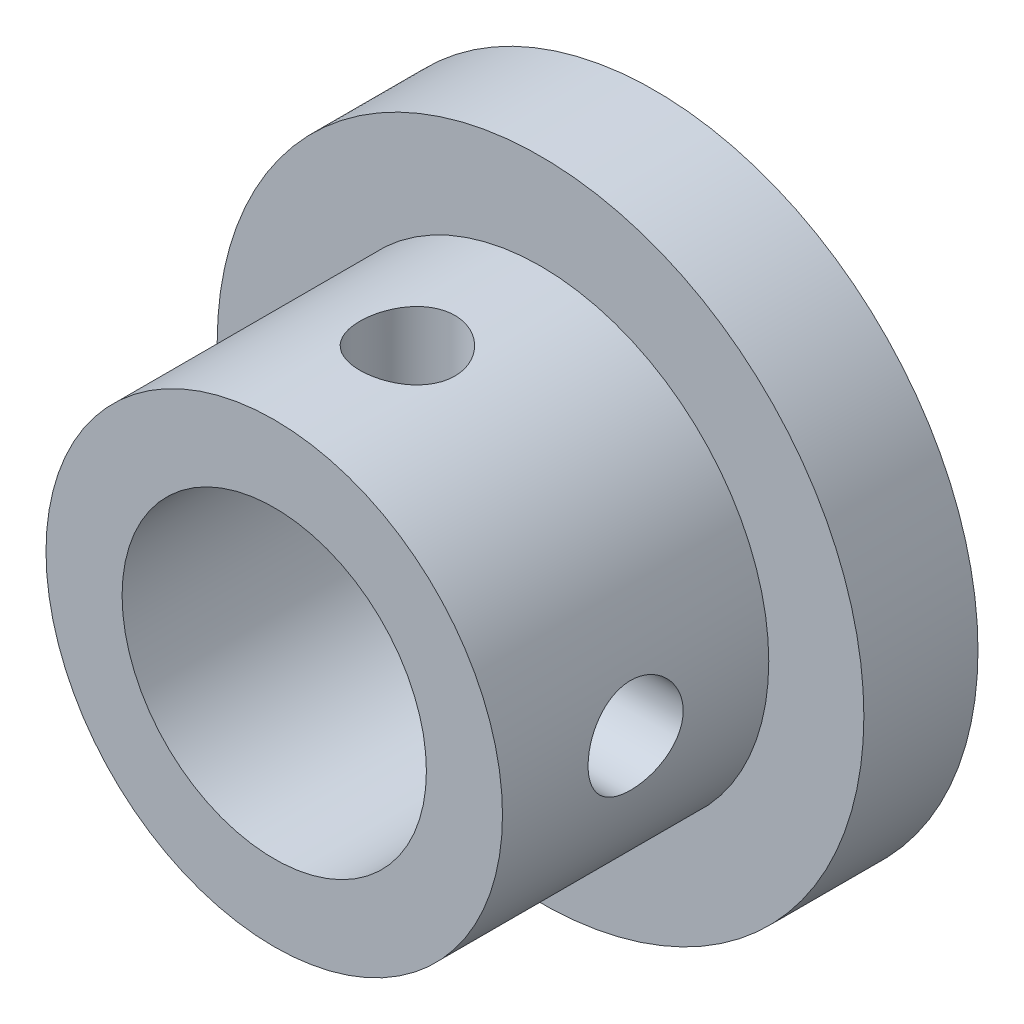
SolidWorks part; units mm, degrees
ref_plane "정면" through (0, 0, 0) normal (0, 0, 1) x (1, 0, 0)
ref_plane "윗면" through (0, 0, 0) normal (0, 1, 0) x (1, 0, 0)
ref_plane "우측면" through (0, 0, 0) normal (1, 0, 0) x (0, 0, -1)
sketch "스케치1" plane through (0, 0, 0) normal (0, 0, 1) x (1, 0, 0)
  circle A0 centre (0, 0) radius 8.5
extrude "보스-돌출1" add sketch "스케치1" along normal blind 3
sketch "스케치2" plane through (0, 0, 3) normal (0, 0, 1) x (1, 0, 0)
  circle A0 centre (0, 0) radius 6
extrude "보스-돌출2" add sketch "스케치2" along normal blind 7 contours A0
sketch "스케치3" plane through (0, 0, 0) normal (0, 0, -1) x (-1, 0, 0)
  circle A0 centre (0, 0) radius 4
extrude "컷-돌출1" cut sketch "스케치3" against normal up to next contours A0
sketch "스케치5" plane through (0, 0, 10) normal (0, 0, 1) x (1, 0, 0)
  line L0 (0, 0) -> (6, 0)
  line L1 (0, 0) -> (0, 6)
  circle A0 centre (0, 0) radius 6 construction
  circle A1 centre (0, 0) radius 6 construction
hole_wizard "M3 나사 구멍1" positions "3D스케치2" profile "스케치6" tap size "M3" standard "KS"
sketch3d "3D스케치2"
  point P0 (0, 6, 6.5)
  point P2 (6, 0, 6.5)
  dimension "D1" = 3.5
  dimension "D2" = 3.5
sketch "스케치6" plane through (0, 6, 6.5) normal (1, 0, 0) x (0, 0, 1)
  line L0 (0, 0) -> (0, 2)
  line L1 (0, 2) -> (1.25, 2)
  line L2 (1.25, 2) -> (1.25, 0)
  line L5 (1.25, 0) -> (0, 0)
  line L11 (0, -6.35) -> (0, 107.95) construction
  dimension "관통 탭 드릴 지름" = 2.5
  dimension "관통 탭 드릴 깊이" = 2
cosmetic thread "구멍 나사산2" parameters "D2"=3
cosmetic thread "구멍 나사산3" parameters "D2"=3
